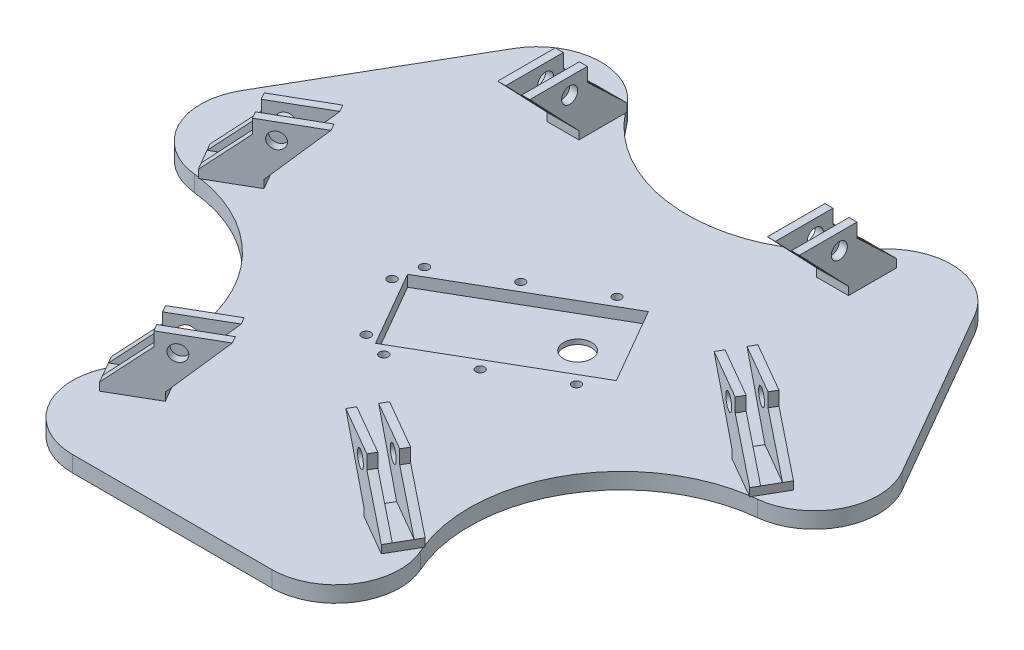
SolidWorks part; units mm, degrees
ref_plane "Front Plane" through (0, 0, 0) normal (0, 0, 1) x (1, 0, 0)
ref_plane "Top Plane" through (0, 0, 0) normal (0, 1, 0) x (1, 0, 0)
ref_plane "Right Plane" through (0, 0, 0) normal (1, 0, 0) x (0, 0, -1)
sketch "Sketch1" plane through (0, 0, 0) normal (0, 1, 0) x (1, 0, 0)
  line L0 (0, 303.1089) -> (0, 0) construction
  line L3 (-175, 0) -> (175, 0) construction
  line L5 (-87.5, 151.5544) -> (87.5, 151.5544) construction
  line L6 (0, 303.1089) -> (-175, 0) construction
  line L7 (0, 303.1089) -> (175, 0) construction
  line L8 (-71.9583, 178.4735) -> (-103.0417, 124.6354)
  line L9 (71.9583, 178.4735) -> (103.0417, 124.6354)
  line L10 (-31.0834, 0) -> (31.0834, 0)
  arc A1 (-38.4488, 180.2173) -> (38.4488, 180.2173) centre (0, 208.1089) ccw
  arc A2 (-49.3484, 28.1481) -> (-87.7972, 94.7434) centre (-92.7276, 47.5) ccw
  arc A3 (87.7972, 94.7434) -> (49.3484, 28.1481) centre (92.7276, 47.5) ccw
  arc A4 (103.0417, 124.6354) -> (87.7972, 94.7434) centre (85.7212, 114.6354) cw
  arc A5 (31.0834, 0) -> (49.3484, 28.1481) centre (31.0834, 20) ccw
  arc A6 (-31.0834, 0) -> (-49.3484, 28.1481) centre (-31.0834, 20) cw
  arc A7 (-103.0417, 124.6354) -> (-87.7972, 94.7434) centre (-85.7212, 114.6354) ccw
  arc A8 (-71.9583, 178.4735) -> (-38.4488, 180.2173) centre (-54.6378, 168.4735) cw
  arc A9 (71.9583, 178.4735) -> (38.4488, 180.2173) centre (54.6378, 168.4735) ccw
  point P15 (133.8638, 71.25)
  point P19 (92.7276, 0)
  point P24 (-92.7276, 0)
  point P27 (-133.8638, 71.25)
  point P30 (-41.1362, 231.8589)
  point P33 (41.1362, 231.8589)
  dimension "D3" = 95
  dimension "D4" = 95
  dimension "D5" = 95
  dimension "D6" = 20
  dimension "D7" = 20
  dimension "D8" = 20
  dimension "D9" = 20
  dimension "D10" = 20
  dimension "D1" = 350
  dimension "D2" = 350
extrude "Boss-Extrude1" add sketch "Sketch1" along normal blind 5
sketch "Sketch2" plane through (0, 0, 0) normal (0, 1, 0) x (1, 0, 0)
  line L1 (-71.9583, 178.4735) -> (-103.0417, 124.6354) construction
  line L2 (103.0417, 124.6354) -> (71.9583, 178.4735) construction
  line L3 (-31.0834, 0) -> (31.0834, 0) construction
  circle A0 centre (0, 208.1089) radius 47.5
  circle A1 centre (-92.7276, 47.5) radius 47.5
  circle A2 centre (92.7276, 47.5) radius 47.5
  dimension "D3" = 95
  dimension "D1" = 95
  dimension "D2" = 95
sketch "Sketch14" plane through (0, 0, 0) normal (0, -1, 0) x (1, 0, 0)
  line L0 (-31.0834, 0) -> (31.0834, 0) construction
  circle A0 centre (-1.4197, -7.5) radius 2.54
  circle A1 centre (-22.2257, -7.5) radius 2.54
  circle A2 centre (26.7743, -7.5) radius 2.54
  circle A3 centre (-16.6597, -58.3) radius 2.54
  circle A4 centre (31.589, -59.3469) radius 2.54
  circle A5 centre (-22.2257, -65.5) radius 2.54
  dimension "D7" = 5.08
  dimension "D8" = 5.08
  dimension "D9" = 5.08
  dimension "D10" = 5.08
  dimension "D11" = 5.08
  dimension "D12" = 5.08
  dimension "D1" = 28.194
  dimension "D2" = 49
  dimension "D3" = 50.8
  dimension "D4" = 15.24
  dimension "D5" = 48.26
  dimension "D6" = 58
  dimension "D13" = 52.07
  dimension "D14" = 7.5
  dimension "D15" = 5.566
extrude "Boss-Extrude5" [suppressed] add sketch "Sketch14" along normal blind 3.81
hole_wizard "1/8 (0.125) Diameter Hole3" [suppressed] positions "Sketch15" profile "Sketch16" hole size "1/8" standard "ANSI Inch"
sketch "Sketch15" [suppressed] plane through (0, -3.81, 0) normal (0, -1, 0) x (-1, 0, 0)
  point P0 (22.2257, 7.5)
  point P3 (1.4197, 7.5)
  point P6 (-26.7743, 7.5)
  point P9 (-31.589, 59.3469)
  point P12 (16.6597, 58.3)
  point P15 (22.2257, 65.5)
sketch "Sketch16" plane through (-22.2257, -3.81, -7.5) normal (1, 0, 0) x (0, 0, -1)
  line L0 (0, 0) -> (0, 4.7629)
  line L1 (0, 4.7629) -> (1.5875, 3.809)
  line L2 (1.5875, 3.809) -> (1.5875, 0)
  line L5 (1.5875, 0) -> (0, 0)
  line L10 (0, 4.7629) -> (-1.5875, 3.809) construction
  line L11 (0, -6.35) -> (0, 107.95) construction
  dimension "Hole Dia." = 3.175
  dimension "Hole Depth" = 3.809
  dimension "Drill Angle" = 118
sketch "Sketch17" [suppressed] plane through (0, -3.81, 0) normal (0, -1, 0) x (1, 0, 0)
  circle A0 centre (-22.2257, -65.5) radius 2.54
  circle A1 centre (-22.2257, -7.5) radius 2.54
extrude "Boss-Extrude6" [suppressed] add sketch "Sketch17" along normal blind 16.51
hole_wizard "1/8 (0.125) Diameter Hole4" [suppressed] positions "Sketch18" profile "Sketch19" hole size "1/8" standard "ANSI Inch"
sketch "Sketch18" [suppressed] plane through (0, -20.32, 0) normal (0, -1, 0) x (-1, 0, 0)
  point P0 (22.2257, 7.5)
  point P3 (22.2257, 65.5)
sketch "Sketch19" plane through (-22.2257, -20.32, -7.5) normal (1, 0, 0) x (0, 0, -1)
  line L0 (0, 0) -> (0, 21.2729)
  line L1 (0, 21.2729) -> (1.5875, 20.319)
  line L2 (1.5875, 20.319) -> (1.5875, 0)
  line L5 (1.5875, 0) -> (0, 0)
  line L10 (0, 21.2729) -> (-1.5875, 20.319) construction
  line L11 (0, -6.35) -> (0, 107.95) construction
  dimension "Hole Dia." = 3.175
  dimension "Hole Depth" = 20.319
  dimension "Drill Angle" = 118
sketch "Sketch25" plane through (0, 5, 0) normal (0, 1, 0) x (1, 0, 0)
  line L0 (-92.7276, 47.5) -> (87.5, 151.5544) construction
  line L1 (103.0417, 124.6354) -> (71.9583, 178.4735) construction
  line L2 (0, 208.1089) -> (0, 0) construction
  line L3 (-31.0834, 0) -> (31.0834, 0) construction
  line L4 (92.7276, 47.5) -> (-87.5, 151.5544) construction
  line L5 (-71.9583, 178.4735) -> (-103.0417, 124.6354) construction
sketch "Sketch26" plane through (0, 5, 0) normal (0, 1, 0) x (1, 0, 0)
  line L1 (0, 208.1089) -> (0, 0) construction
  line L3 (92.7276, 47.5) -> (-87.5, 151.5544) construction
  point P0 (0, 101.0363)
sketch "Sketch27" plane through (0, 5, 0) normal (0, 1, 0) x (1, 0, 0)
  line L0 (-91.0069, 102.8291) -> (-86.0069, 94.1689)
  line L1 (-86.0069, 94.1689) -> (-73.0165, 101.6689)
  line L2 (-73.0165, 101.6689) -> (-78.0165, 110.3291)
  line L3 (-78.0165, 110.3291) -> (-91.0069, 102.8291)
  line L5 (-75.5165, 105.999) -> (-88.5069, 98.499) construction
  line L6 (-92.7276, 47.5) -> (87.5, 151.5544) construction
  dimension "D1" = 10
  dimension "D2" = 15
  dimension "D3" = 42.0561
extrude "Boss-Extrude11" add sketch "Sketch27" along normal blind 2.5
sketch "Sketch28" plane through (-62.278, 0, -107.8687) normal (0.5, 0, 0.866) x (0.866, 0, -0.5)
  line L0 (-27.3997, 7.5) -> (-15.0267, 19.2174)
  line L1 (-15.0267, 19.2174) -> (-15.0267, 23.5585)
  line L2 (-15.0267, 23.5585) -> (2.9274, 23.5585)
  line L3 (2.9274, 23.5585) -> (-12.3997, 7.5)
  line L4 (-12.3997, 7.5) -> (-27.3997, 7.5)
extrude "Boss-Extrude12" add sketch "Sketch28" against normal blind 2.5
ref_plane "Plane2" through (-64.778, 0, -112.1989) normal (0.5, 0, 0.866) x (0.866, 0, -0.5)
ref_plane "Plane3" through (-43.75, 0, -75.7772) normal (0.5, 0, 0.866) x (0.866, 0, -0.5)
sketch "Sketch29" plane through (-63.528, 0, -110.0338) normal (-0.5, 0, -0.866) x (-0.866, 0, 0.5)
  line L0 (-2.9274, 23.5585) -> (15.0267, 23.5585) construction
  line L1 (15.0267, 23.5585) -> (15.0267, 19.2174) construction
  circle A0 centre (9.5267, 18.5585) radius 2.5
  dimension "D1" = 5
  dimension "D2" = 5.5
extrude "Cut-Extrude1" cut sketch "Sketch29" against normal through all both and the other way through all
mirror "Mirror4" about plane through (-64.778, 0, -112.1989) normal (0.5, 0, 0.866) of "Boss-Extrude12", "Cut-Extrude1"
mirror "Mirror5" about plane through (-43.75, 0, -75.7772) normal (0.5, 0, 0.866) of "Boss-Extrude11", "Mirror4", "Boss-Extrude12", "Cut-Extrude1"
mirror "Mirror6" about plane through (0, 0, 0) normal (1, 0, 0) of "Boss-Extrude11", "Mirror5", "Boss-Extrude12", "Mirror4"
mirror "Mirror7" about plane through (-43.75, 0, -75.7772) normal (0.5, 0, 0.866) of "Mirror6", "Mirror4", "Mirror5"
sketch "Sketch30" plane through (0, 5, 0) normal (0, 1, 0) x (1, 0, 0)
  line L0 (87.5, 151.5544) -> (-20.3202, 89.3044)
  line L1 (20.1403, 128.4273) -> (33.7915, 104.7828)
  line L2 (103.0417, 124.6354) -> (71.9583, 178.4735) construction
  line L6 (20.1403, 128.4273) -> (-27.4922, 100.9267)
  line L7 (-27.4922, 100.9267) -> (-13.841, 77.2822)
  line L9 (33.7915, 104.7828) -> (-13.841, 77.2822)
  line L11 (33.245, 104.9292) -> (26.2445, 117.0546) construction
  line L12 (26.2445, 117.0546) -> (22.3195, 123.8529) construction
  line L13 (19.9939, 127.8809) -> (-26.9457, 100.7803) construction
  line L14 (-26.9457, 100.7803) -> (-13.6946, 77.8286) construction
  line L15 (30.8202, 103.5292) -> (-10.6635, 79.5786) construction
  line L16 (30.8202, 103.5292) -> (33.245, 104.9292) construction
  line L17 (22.3195, 123.8529) -> (19.9939, 127.8809) construction
  line L18 (-10.6635, 79.5786) -> (-13.6946, 77.8286) construction
  line L19 (-13.841, 77.2822) -> (20.1403, 128.4273) construction
  line L20 (33.7915, 104.7828) -> (-27.4922, 100.9267) construction
  line L21 (0, 0) -> (0, 70.9063) construction
  dimension "D1" = 124.5
  dimension "D2" = 55.0012
  dimension "D3" = 0.4
  dimension "D4" = 0.4
  dimension "D5" = 0.4
  dimension "D6" = 0.4
  dimension "D7" = 60
extrude "Cut-Extrude2" cut sketch "Sketch30" against normal blind 3.5
sketch "Sketch31" plane through (0, 1.5, 0) normal (0, 1, 0) x (1, 0, 0)
  line L0 (-27.4922, 100.9267) -> (-13.841, 77.2822) construction
  line L1 (3.1497, 102.8547) -> (-13.841, 132.2834) construction
  line L2 (20.1403, 128.4273) -> (33.7915, 104.7828) construction
  line L3 (20.1403, 128.4273) -> (33.7915, 104.7828) construction
  line L4 (26.9659, 116.6051) -> (-20.6666, 89.1044) construction
  line L5 (-27.4922, 100.9267) -> (-13.841, 77.2822) construction
  circle A0 centre (-9.8413, 95.3544) radius 4 construction
  circle A1 centre (-9.8413, 95.3544) radius 4.4 construction
  circle A2 centre (16.1406, 110.3551) radius 4.4
  dimension "D1" = 12.5
extrude "Cut-Extrude3" cut sketch "Sketch31" against normal through all
sketch "Sketch33" plane through (0, 5, 0) normal (0, 1, 0) x (1, 0, 0)
  line L0 (-3.6759, 114.677) -> (7.3905, 95.5094) construction
  line L1 (20.1403, 128.4273) -> (-27.4922, 100.9267) construction
  line L2 (20.1403, 128.4273) -> (-27.4922, 100.9267) construction
  circle A2 centre (11.2866, 127.52) radius 1.35
  circle A12 centre (-7.766, 116.52) radius 1.35
  circle A13 centre (-28.6038, 97.2146) radius 1.385
  circle A14 centre (-17.6038, 78.1621) radius 1.385
  circle A15 centre (-9.5186, 75.5555) radius 1.35
  circle A16 centre (9.534, 86.5555) radius 1.35
  circle A17 centre (28.5866, 97.5555) radius 1.35
  circle A18 centre (-26.8186, 105.52) radius 1.385
extrude "Cut-Extrude4" cut sketch "Sketch33" against normal through all
sketch "Sketch34" plane through (0, 5, 0) normal (0, 1, 0) x (1, 0, 0)
  line L0 (26.9659, 116.6051) -> (107.7073, 163.2211)
  line L1 (20.1403, 128.4273) -> (33.7915, 104.7828) construction
ref_plane "Plane4" through (-43.75, 0, -75.7772) normal (0.5, 0, 0.866) x (0.866, 0, -0.5)
sketch "Sketch35" plane through (0, 5, 0) normal (0, 1, 0) x (1, 0, 0)
  line L0 (0, 0) -> (0, 160.6089)
  line L1 (-31.0834, 0) -> (31.0834, 0) construction
  line L2 (51.5914, 71.25) -> (-87.5, 151.5544)
  line L4 (-71.9583, 178.4735) -> (-103.0417, 124.6354) construction
  arc A0 (-37.0561, 178.3919) -> (37.0561, 178.3919) centre (0, 208.1089) ccw construction
  arc A2 (85.52, 94.45) -> (48.4639, 30.267) centre (92.7276, 47.5) ccw construction
ref_plane "Plane5" through (0, 0, 0) normal (1, 0, 0) x (0, 0, -1)
ref_plane "Plane6" through (43.75, 0, -75.7772) normal (0.5, 0, -0.866) x (-0.866, 0, -0.5)
equation "\"D2@Sketch1\"=\"D1@Sketch1\""
equation "\"D3@Sketch2\"=\"D1@Sketch2\""
equation "\"D2@Sketch2\"=\"D1@Sketch2\""
equation "\"D8@Sketch14\"=\"D7@Sketch14\""
equation "\"D9@Sketch14\"=\"D7@Sketch14\""
equation "\"D10@Sketch14\"=\"D7@Sketch14\""
equation "\"D11@Sketch14\"=\"D7@Sketch14\""
equation "\"D12@Sketch14\"=\"D7@Sketch14\""
equation "\"D7@Sketch1\"=\"D6@Sketch1\""
equation "\"D8@Sketch1\"=\"D7@Sketch1\""
equation "\"D9@Sketch1\"=\"D6@Sketch1\""
equation "\"D10@Sketch1\"=\"D8@Sketch1\""
